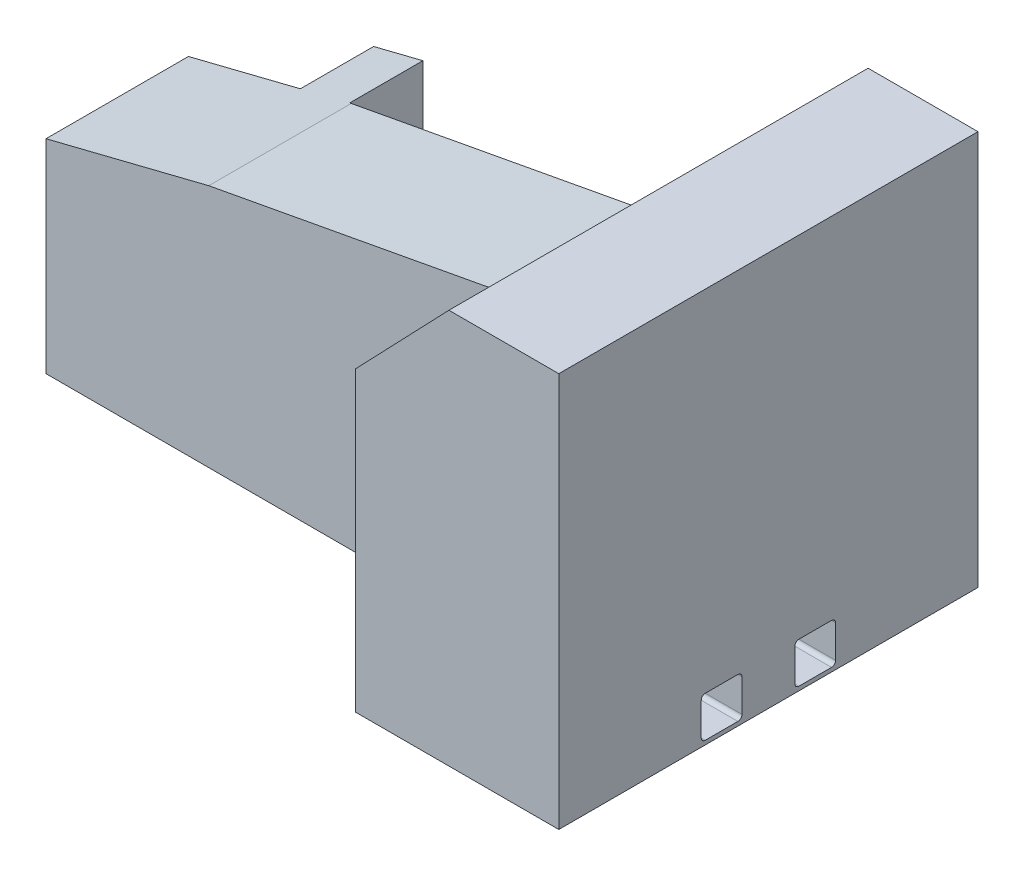
SolidWorks part; units mm, degrees
material "Custom Plastic"
ref_plane "Front Plane" through (0, 0, 0) normal (0, 0, 1) x (1, 0, 0)
ref_plane "Top Plane" through (0, 0, 0) normal (0, 1, 0) x (1, 0, 0)
ref_plane "Right Plane" through (0, 0, 0) normal (1, 0, 0) x (0, 0, -1)
sketch "Sketch1" plane through (0, 0, 0) normal (0, 0, 1) x (1, 0, 0)
  line L0 (-800, 0) -> (800, 0)
  line L1 (-800, 0) -> (-800, 500)
  line L2 (-400, 0) -> (-400, 600)
  line L3 (530, 0) -> (530, 970)
  line L4 (300, 0) -> (300, 730)
  line L5 (-800, 500) -> (-400, 600)
  line L6 (-400, 600) -> (300, 730)
  line L7 (300, 730) -> (530, 970)
  line L8 (800, 0) -> (530, 970)
  line L9 (-800, 500) -> (-800, 970)
  line L10 (-800, 970) -> (530, 970)
  dimension "D1" = 1600
  dimension "D2" = 500
  dimension "D3" = 400
  dimension "D4" = 800
  dimension "D5" = 600
  dimension "D6" = 270
  dimension "D7" = 500
  dimension "D8" = 970
  dimension "D9" = 730
sketch "Sketch2" plane through (0, 0, 0) normal (0, 1, 0) x (1, 0, 0)
  line L0 (800, -515) -> (800, 515)
  line L2 (800, -515) -> (300, -515)
  line L3 (300, -515) -> (300, -175)
  line L4 (300, -175) -> (-800, -175)
  line L5 (-800, -175) -> (-800, 175)
  line L6 (-800, 175) -> (-404, 175)
  line L7 (-404, 175) -> (-404, 355)
  line L8 (-404, 355) -> (-525, 355)
  line L9 (-525, 355) -> (-525, 175)
  line L10 (-525, 175) -> (300, 175)
  line L11 (300, 175) -> (300, 515)
  line L12 (300, 515) -> (800, 515)
  dimension "D1" = 800
  dimension "D2" = 500
  dimension "D3" = 175
  dimension "D4" = 175
  dimension "D5" = 530
  dimension "D6" = 121
  dimension "D7" = 500
  dimension "D8" = 350
  dimension "D9" = 1600
  dimension "D10" = 1030
  dimension "D11" = 515
  dimension "D12" = 275
extrude "Boss-Extrude1" add sketch "Sketch2" along normal blind 970 contours L12 L11 L10 L6 L5 L4 L3 L2 L0 | L8 L9 L6 L7
extrude "Cut-Extrude1" cut sketch "Sketch1" against normal through all both and the other way through all contours L10 L9 L5 L6 L7
sketch "Sketch3" plane through (-800, 0, 0) normal (-1, 0, 0) x (0, 0, 1)
  line L0 (-165, 0) -> (-65, 0)
  line L1 (175, 0) -> (-175, 0) construction
  line L2 (-55, 10) -> (-55, 120)
  line L3 (-55, 120) -> (-175, 120)
  line L4 (-175, 730) -> (-175, 0) construction
  line L5 (-175, 120) -> (-175, 10)
  line L11 (-165, 100) -> (-165, 20)
  line L12 (-155, 10) -> (-75, 10)
  line L13 (-65, 20) -> (-65, 100)
  line L14 (-75, 110) -> (-155, 110)
  line L19 (0, 137.8655) -> (0, -90.7951) construction
  line L20 (75, 110) -> (155, 110)
  line L21 (65, 20) -> (65, 100)
  line L22 (155, 10) -> (75, 10)
  line L23 (165, 100) -> (165, 20)
  line L24 (175, 120) -> (175, 10)
  line L25 (55, 120) -> (175, 120)
  line L26 (55, 10) -> (55, 120)
  line L27 (165, 0) -> (65, 0)
  arc A0 (175, 10) -> (165, 0) centre (165, 10) cw
  arc A1 (155, 10) -> (165, 20) centre (155, 20) ccw
  arc A2 (65, 20) -> (75, 10) centre (75, 20) ccw
  arc A3 (55, 10) -> (65, 0) centre (65, 10) ccw
  arc A4 (-65, 0) -> (-55, 10) centre (-65, 10) ccw
  arc A5 (-165, 0) -> (-175, 10) centre (-165, 10) cw
  arc A6 (-165, 20) -> (-155, 10) centre (-155, 20) ccw
  arc A7 (-75, 10) -> (-65, 20) centre (-75, 20) ccw
  arc A8 (-65, 100) -> (-75, 110) centre (-75, 100) ccw
  arc A9 (-165, 100) -> (-155, 110) centre (-155, 100) cw
  arc A10 (155, 110) -> (165, 100) centre (155, 100) cw
  arc A11 (75, 110) -> (65, 100) centre (75, 100) ccw
  point P27 (175, 0)
  point P30 (165, 10)
  point P33 (65, 10)
  point P36 (55, 0)
  point P39 (-55, 0)
  point P42 (-175, 0)
  point P45 (-165, 10)
  point P48 (-65, 10)
  point P51 (-65, 110)
  point P54 (-165, 110)
  point P57 (165, 110)
  point P60 (65, 110)
  dimension "D3" = 10
  dimension "D4" = 10
  dimension "D1" = 120
  dimension "D2" = 120
  dimension "D5" = 100
  dimension "D6" = 100
  dimension "D8" = 10
  dimension "D9" = 10
extrude "Cut-Extrude5" cut sketch "Sketch3" against normal blind 1625 contours A9 L11 A6 L12 A7 L13 A8 L14 | L21 A2 L22 A1 L23 L20
sketch "Sketch4" plane through (0, 0, 0) normal (0, -1, 0) x (1, 0, 0)
  line L0 (-1069.2255, 0) -> (880.5229, 0) construction
  line L1 (0, 391.8823) -> (0, -321.383) construction
  line L2 (300, 175) -> (-800, 175) construction
  line L3 (-800, -175) -> (-525, -175) construction
  circle A0 centre (-498.5, 115) radius 8.5
  circle A1 centre (-501, -115) radius 8.5
  circle A2 centre (501, -115) radius 8.5
  circle A3 centre (498.5, 115) radius 8.5
  dimension "D1" = 17
  dimension "D4" = 17
  dimension "D2" = 498.5
  dimension "D3" = 60
  dimension "D5" = 501
  dimension "D6" = 60
extrude "Cut-Extrude6" cut sketch "Sketch4" against normal blind 78
